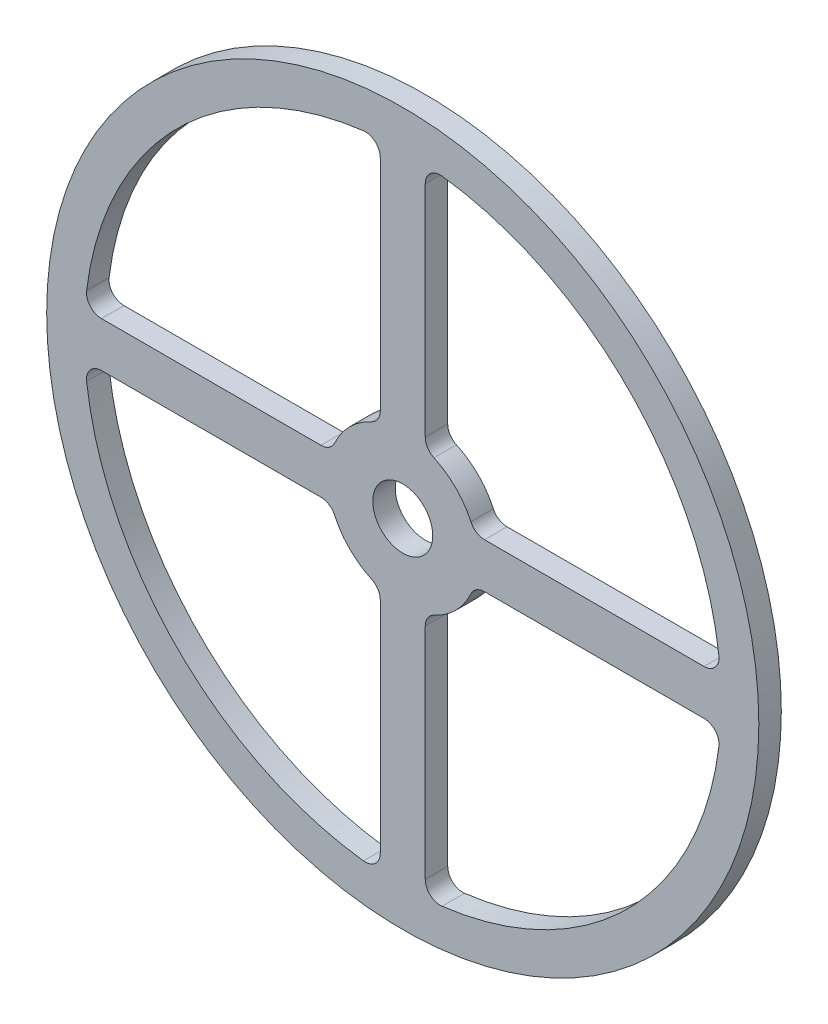
SolidWorks part; units mm, degrees
ref_plane "前视基准面" through (0, 0, 0) normal (0, 0, 1) x (1, 0, 0)
ref_plane "上视基准面" through (0, 0, 0) normal (0, 1, 0) x (1, 0, 0)
ref_plane "右视基准面" through (0, 0, 0) normal (1, 0, 0) x (0, 0, -1)
sketch "草图1" plane through (0, 0, 0) normal (0, 0, 1) x (1, 0, 0)
  line L0 (3, 42.394) -> (3, 9.5394)
  line L1 (9.5394, 3) -> (42.394, 3)
  line L2 (0, 72.2615) -> (0, -79.5295) construction
  line L3 (-78.2791, 0) -> (88.2263, 0) construction
  line L4 (-9.5394, -3) -> (-42.394, -3)
  line L5 (9.5394, -3) -> (42.394, -3)
  line L7 (-3, 9.5394) -> (-3, 42.394)
  line L8 (-3, -9.5394) -> (-3, -42.394)
  line L9 (3, -9.5394) -> (3, -42.394)
  line L10 (-9.5394, 3) -> (-42.394, 3)
  circle A0 centre (0, 0) radius 47.5
  arc A1 (-3, 42.394) -> (-42.394, 3) centre (0, 0) ccw
  arc A2 (3, -42.394) -> (42.394, -3) centre (0, 0) ccw
  arc A3 (-42.394, -3) -> (-3, -42.394) centre (0, 0) ccw
  arc A4 (42.394, 3) -> (3, 42.394) centre (0, 0) ccw
  arc A5 (-3, 9.5394) -> (-9.5394, 3) centre (0, 0) ccw
  circle A6 centre (0, 0) radius 4
  arc A7 (9.5394, 3) -> (3, 9.5394) centre (0, 0) ccw
  arc A8 (-9.5394, -3) -> (-3, -9.5394) centre (0, 0) ccw
  arc A9 (3, -9.5394) -> (9.5394, -3) centre (0, 0) ccw
  dimension "D1" = 95
  dimension "D2" = 85
  dimension "D5" = 8
  dimension "D6" = 20
  dimension "D3" = 3
  dimension "D4" = 3
extrude "凸台-拉伸1" add sketch "草图1" along normal blind 3
fillet "圆角1" radius 2 1 edges at (3, 42.394, 1.5)
fillet "圆角2" radius 2 7 edges at (42.394, 3, 1.5) (42.394, -3, 1.5) (3, -42.394, 1.5) (-3, -42.394, 1.5) (-42.394, -3, 1.5) (-42.394, 3, 1.5) (-3, 42.394, 1.5)
fillet "圆角4" radius 2 8 edges at (3, -9.5394, 1.5) (-3, -9.5394, 1.5) (-9.5394, -3, 1.5) (-9.5394, 3, 1.5) (-3, 9.5394, 1.5) (3, 9.5394, 1.5) (9.5394, 3, 1.5) (9.5394, -3, 1.5)
